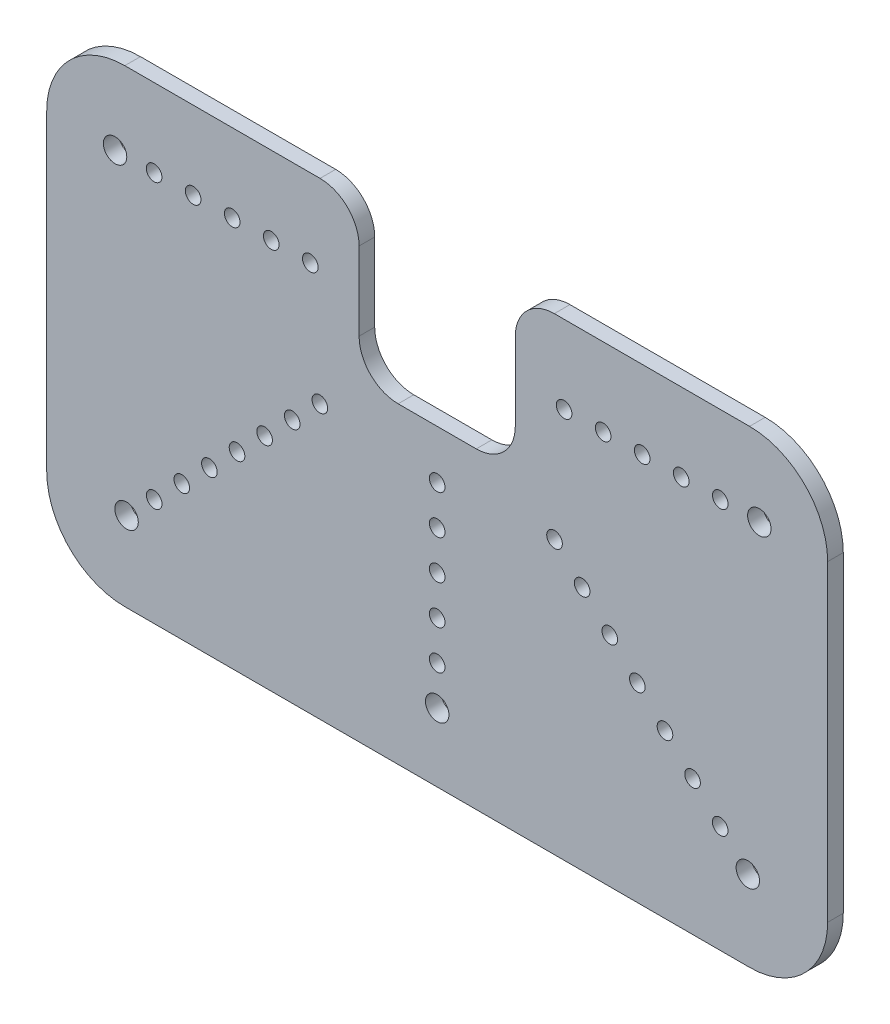
SolidWorks part; units mm, degrees
ref_plane "Front Plane" through (0, 0, 0) normal (0, 0, 1) x (1, 0, 0)
ref_plane "Top Plane" through (0, 0, 0) normal (0, 1, 0) x (1, 0, 0)
ref_plane "Right Plane" through (0, 0, 0) normal (1, 0, 0) x (0, 0, -1)
sketch "Sketch1" plane through (0, 0, 0) normal (0, 0, 1) x (1, 0, 0)
  line L0 (4.5495, 16.5783) -> (14.5495, 16.5783) construction
  line L1 (32.0495, 36.5783) -> (-47.9505, 36.5783)
  line L2 (32.0495, 36.5783) -> (32.0495, -83.4217)
  line L3 (32.0495, -83.4217) -> (-167.9505, -83.4217)
  line L4 (-167.9505, 36.5783) -> (-167.9505, -83.4217)
  line L8 (82.0495, -83.4217) -> (-167.9505, -83.4217)
  line L10 (-87.9505, -3.4217) -> (-47.9505, -3.4217)
  line L11 (-87.9505, -3.4217) -> (-87.9505, 36.5783)
  line L13 (-47.9505, -3.4217) -> (-47.9505, 36.5783)
  line L16 (-87.9505, 36.5783) -> (-167.9505, 36.5783)
  circle A0 centre (14.5495, 16.5783) radius 3
  circle A1 centre (-9.6142, -41.758) radius 2
  circle A2 centre (-16.6853, -34.687) radius 2
  circle A3 centre (-23.7563, -27.6159) radius 2
  circle A4 centre (-30.8274, -20.5448) radius 2
  circle A5 centre (-37.8985, -13.4738) radius 2
  circle A8 centre (-35.4505, 16.5783) radius 2
  circle A9 centre (-25.4505, 16.5783) radius 2
  circle A10 centre (-15.4505, 16.5783) radius 2
  circle A11 centre (-5.4505, 16.5783) radius 2
  circle A12 centre (4.5495, 16.5783) radius 2
  circle A14 centre (-2.5431, -48.8291) radius 2
  circle A15 centre (-67.9505, -65.9217) radius 3
  circle A16 centre (-67.9505, -55.9217) radius 2
  circle A17 centre (-67.9505, -45.9217) radius 2
  circle A18 centre (-67.9505, -35.9217) radius 2
  circle A19 centre (-67.9505, -25.9217) radius 2
  circle A20 centre (-67.9505, -15.9217) radius 2
  circle A22 centre (4.5279, -55.9002) radius 2
  circle A23 centre (-126.2868, -41.758) radius 2
  circle A24 centre (-119.2157, -34.687) radius 2
  circle A25 centre (-112.1447, -27.6159) radius 2
  circle A26 centre (-105.0736, -20.5448) radius 2
  circle A27 centre (-98.0025, -13.4738) radius 2
  circle A30 centre (11.599, -62.9712) radius 3
  circle A31 centre (-150.4505, 16.5783) radius 3
  circle A32 centre (-140.4505, 16.5783) radius 2
  circle A33 centre (-130.4505, 16.5783) radius 2
  circle A34 centre (-120.4505, 16.5783) radius 2
  circle A35 centre (-110.4505, 16.5783) radius 2
  circle A36 centre (-100.4505, 16.5783) radius 2
  circle A38 centre (-133.3579, -48.8291) radius 2
  circle A39 centre (-140.4289, -55.9002) radius 2
  circle A40 centre (-147.5, -62.9712) radius 3
  point P0 (-67.9505, 16.5783)
  point P85 (-67.9505, 16.5783)
  point P89 (-67.9505, 16.5783)
  point P95 (-67.9505, 16.5783)
  dimension "D2" = 10
  dimension "D3" = 200
  dimension "D4" = 120
extrude "Boss-Extrude1" add sketch "Sketch1" along normal blind 4 contours L11 L16 L4 L3 L2 L1 L13 L10 A40 A39 A38 A36 A35 A34 A33 A32 A31 A30 A27 A26 A25 A24 A23 A22 A20 A19 A18 A17 A16
fillet "Fillet1" radius 10 2 edges at (-47.9505, -3.4217, 2) (-87.9505, -3.4217, 2)
fillet "Fillet2" radius 10 2 edges at (-47.9505, 36.5783, 2) (-87.9505, 36.5783, 2)
fillet "Fillet3" radius 20 4 edges at (32.0495, 36.5783, 2) (32.0495, -83.4217, 2) (-167.9505, 36.5783, 2) (-167.9505, -83.4217, 2)
